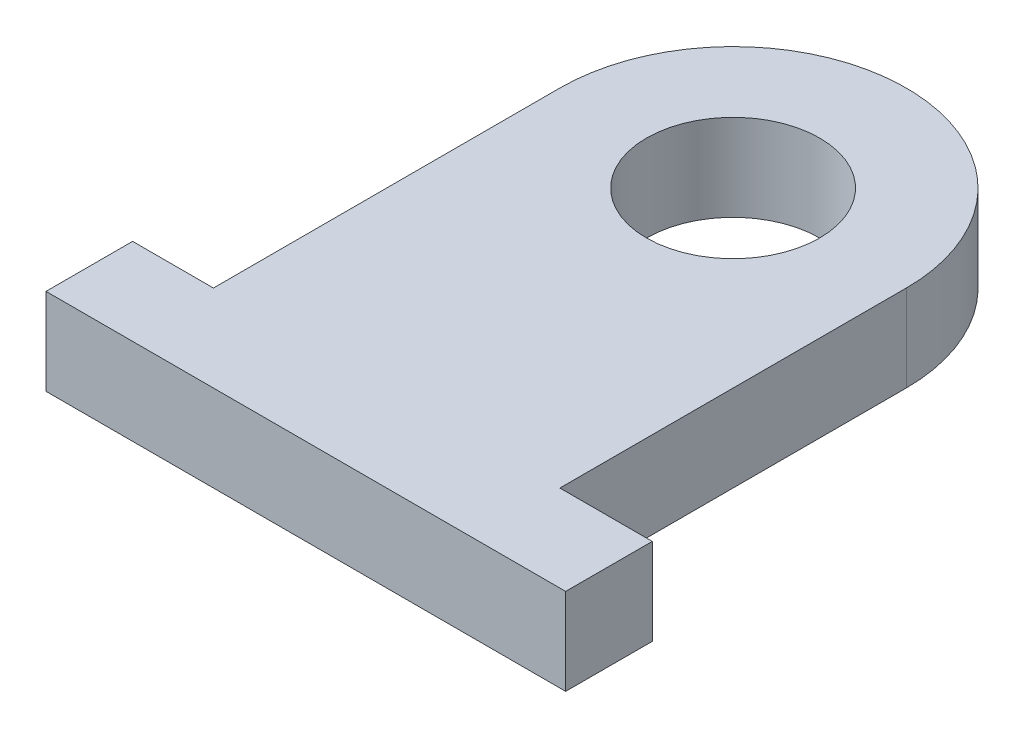
SolidWorks part; units mm, degrees
ref_plane "Front Plane" through (0, 0, 0) normal (0, 0, 1) x (1, 0, 0)
ref_plane "Top Plane" through (0, 0, 0) normal (0, 1, 0) x (1, 0, 0)
ref_plane "Right Plane" through (0, 0, 0) normal (1, 0, 0) x (0, 0, -1)
sketch "Sketch2" plane through (0, 0, 0) normal (0, 1, 0) x (1, 0, 0)
  line L0 (-10, 0) -> (-10, -20)
  line L1 (10, 0) -> (10, -20)
  line L2 (-10, -20) -> (10, -20)
  circle A0 centre (0, 0) radius 5
  arc A1 (-10, 0) -> (10, 0) centre (0, 0) cw
  dimension "D1" = 10
  dimension "D2" = 10
  dimension "D3" = 20
extrude "Boss-Extrude1" add sketch "Sketch2" along normal blind 5
sketch "Sketch3" plane through (0, 0, 20) normal (0, 0, 1) x (1, 0, 0)
  line L0 (-10, 5) -> (10, 5) construction
  line L1 (-14.6658, 5) -> (15.3342, 5)
  line L2 (-14.6658, 5) -> (-14.6658, 0)
  line L3 (-14.6658, 0) -> (15.3342, 0)
  line L4 (15.3342, 5) -> (15.3342, 0)
  line L5 (-14.6658, 5) -> (15.3342, 0) construction
  line L6 (-14.6658, 0) -> (15.3342, 5) construction
  line L7 (-10, 0) -> (10, 0) construction
  point P0 (0.3342, 2.5)
  dimension "D1" = 30
extrude "Boss-Extrude2" add sketch "Sketch3" along normal blind 5
